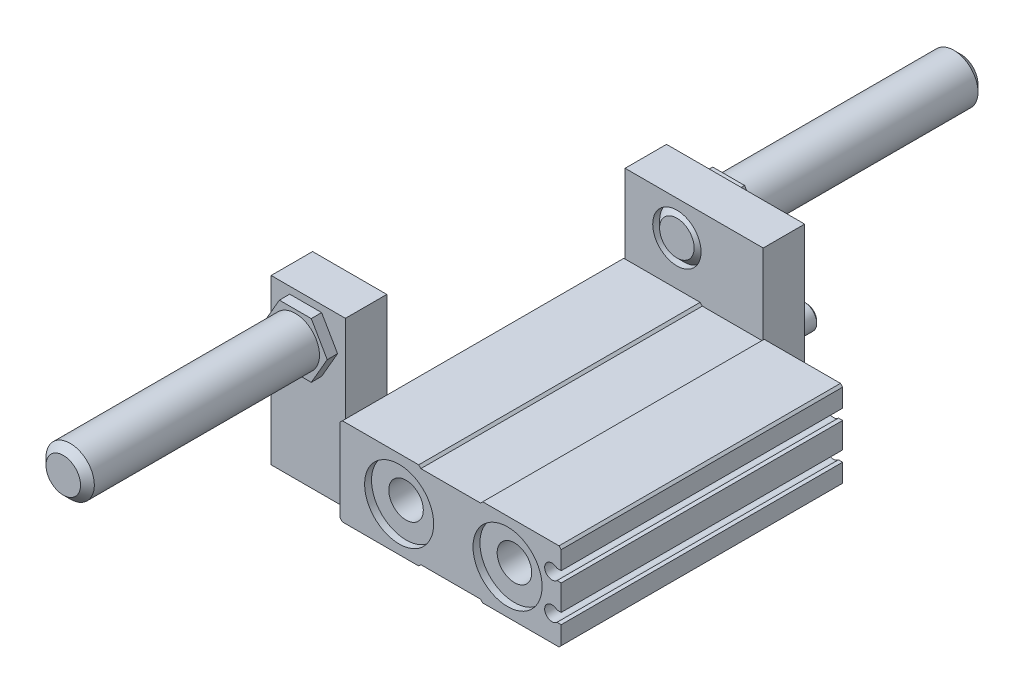
SolidWorks part; units mm, degrees
ref_plane "Front" through (0, 0, 0) normal (0, 0, 1) x (1, 0, 0)
ref_plane "Top" through (0, 0, 0) normal (0, 1, 0) x (1, 0, 0)
ref_plane "Right" through (0, 0, 0) normal (1, 0, 0) x (0, 0, -1)
ref_plane "Plane4" through (0, 0, 0) normal (0, 0, 1) x (-1, 0, 0)
sketch "Sketch1" plane through (0, 0, 48.65) normal (0, 0, 1) x (-1, 0, 0)
  line L0 (31.365, 12.6873) -> (32, 12.0523)
  line L1 (-8.636, 12.0523) -> (8.636, 12.0523)
  line L2 (31.365, 12.6873) -> (9.271, 12.6873)
  line L3 (-9.271, 12.6873) -> (-31.365, 12.6873)
  line L4 (8.636, 12.0523) -> (9.271, 12.6873)
  line L5 (-8.636, 12.0523) -> (-9.271, 12.6873)
  line L6 (-32, 12.0523) -> (-32, 6.7691)
  line L7 (-32, -12.0523) -> (-31.365, -12.6873)
  line L8 (-8.636, -12.0523) -> (-9.271, -12.6873)
  line L9 (-32, 3.6957) -> (-32, -3.6957)
  line L10 (-32, -6.7691) -> (-32, -12.0523)
  line L11 (-32, 12.0523) -> (-31.365, 12.6873)
  line L12 (32, 12.0523) -> (32, -12.0523)
  line L14 (-50, 0) -> (50, 0) construction
  line L15 (-9.271, -12.6873) -> (-31.365, -12.6873)
  line L16 (-30.7919, -6.7691) -> (-32, -6.7691)
  line L18 (-8.636, -12.0523) -> (8.636, -12.0523)
  line L19 (8.636, -12.0523) -> (9.271, -12.6873)
  line L20 (32, -12.0523) -> (31.365, -12.6873)
  line L22 (-32, 0) -> (32, 0) construction
  line L23 (0, 0) -> (0, 12.0523) construction
  line L26 (31.365, -12.6873) -> (9.271, -12.6873)
  line L27 (-30.7919, -3.6957) -> (-32, -3.6957)
  line L28 (-30.7919, 3.6957) -> (-32, 3.6957)
  line L29 (-30.7919, 6.7691) -> (-32, 6.7691)
  arc A0 (-30.7919, 3.6957) -> (-30.7919, 6.7691) centre (-29.3301, 5.2324) ccw
  arc A1 (-30.7919, -6.7691) -> (-30.7919, -3.6957) centre (-29.3301, -5.2324) ccw
  circle A2 centre (-16.4592, 0) radius 13.8938 construction
  dimension "D5" = 4.2418
  dimension "D9" = 5.2324
  dimension "D7" = 13.8938
  dimension "D1" = 25.3746
  dimension "D2" = 45
  dimension "D3" = 0.635
  dimension "D4" = 16.4592
  dimension "D6" = 18.542
  dimension "D8" = 3.0734
extrude "Base-Extrude" add sketch "Sketch1" along normal up to surface (81.5 mm away)
ref_plane "Plane8" through (0, 0, 46.65) normal (0, 0, 1) x (1, 0, 0)
sketch "Sketch2" plane through (0, 0, 48.65) normal (0, 0, -1) x (-1, 0, 0)
  line L0 (47.3, 0) -> (-47.3, 0) construction
  line L5 (0, 12.0523) -> (0, -12.0523) construction
  line L6 (8.636, 12.0523) -> (-8.636, 12.0523) construction
  line L7 (-8.636, -12.0523) -> (8.636, -12.0523) construction
  circle A0 centre (-16.4592, 0) radius 10
  circle A1 centre (14.9352, 0) radius 10
  dimension "D1" = 20
  dimension "D3" = 16.4592
  dimension "D2" = 31.3944
extrude "Cut-Extrude1" cut sketch "Sketch2" along normal up to surface (80.2 mm away)
sketch "Sketch4" plane through (0, 0, 46.65) normal (0, 0, 1) x (1, 0, 0)
  circle A2 centre (16.4592, 0) radius 10 construction
  circle A3 centre (-14.9352, 0) radius 10 construction
  circle A4 centre (16.4592, 0) radius 10
  circle A5 centre (-14.9352, 0) radius 10
extrude "Boss-Extrude1" add sketch "Sketch4" against normal blind 10
sketch "Sketch19" plane through (0, 0, 46.65) normal (0, 0, 1) x (1, 0, 0)
  circle A0 centre (16.4592, 0) radius 5
  circle A1 centre (-14.9352, 0) radius 5
  circle A2 centre (-14.9352, 0) radius 10 construction
  circle A3 centre (16.4592, 0) radius 10 construction
  dimension "D1" = 10
extrude "Cut-Extrude3" cut sketch "Sketch19" against normal up to next
hole_wizard "1/4-20 Tapped Hole1" positions "Sketch21" profile "Sketch20" tap size "1/4-20" standard "Ansi Inch"
sketch "Sketch21" plane through (0, -12.0523, 0) normal (0, -1, 0) x (1, 0, 0)
  point P0 (0, 23.15)
  point P1 (0, -6.85)
sketch "Sketch20" plane through (0, -12.0523, 23.15) normal (1, 0, 0) x (0, 0, -1)
  line L0 (0, 0) -> (0, 19.8218)
  line L1 (0, 19.8218) -> (2.5527, 18.288)
  line L2 (2.5527, 18.288) -> (2.5527, 11.938)
  line L3 (2.5527, 11.938) -> (3.175, 11.938)
  line L4 (3.175, 11.938) -> (3.175, 0)
  line L5 (3.175, 0) -> (0, 0)
  line L10 (0, 19.8218) -> (-2.5527, 18.288) construction
  line L11 (0, -6.35) -> (0, 107.95) construction
  dimension "Tap Drill Dia." = 5.1054
  dimension "Tap Drill Depth" = 18.288
  dimension "Thread Dia." = 6.35
  dimension "Thread Depth" = 11.938
  dimension "Drill Angle" = 118
hole_wizard "#10-32 Tapped Hole2" positions "Sketch23" profile "Sketch22" tap size "#10-32" standard "Ansi Inch"
sketch "Sketch23" plane through (0, 0, -32.85) normal (0, 0, -1) x (-1, 0, 0)
  line L0 (9.271, -12.6873) -> (31.365, -12.6873) construction
  point P0 (28, -7.5873)
  point P1 (28, 7.8127)
  point P2 (-4.5, -7.5873)
  point P3 (-4.5, 7.8127)
  dimension "D1" = 5.1
  dimension "D2" = 15.4
  dimension "D3" = 32.5
  dimension "D4" = 28
sketch "Sketch22" plane through (-28, -7.5873, -32.85) normal (1, 0, 0) x (0, 1, 0)
  line L0 (0, 0) -> (0, 15.0817)
  line L1 (0, 15.0817) -> (2.0193, 13.8684)
  line L2 (2.0193, 13.8684) -> (2.0193, 9.906)
  line L3 (2.0193, 9.906) -> (2.413, 9.906)
  line L4 (2.413, 9.906) -> (2.413, 0)
  line L5 (2.413, 0) -> (0, 0)
  line L10 (0, 15.0817) -> (-2.0193, 13.8684) construction
  line L11 (0, -6.35) -> (0, 107.95) construction
  dimension "Tap Drill Dia." = 4.0386
  dimension "Tap Drill Depth" = 13.8684
  dimension "Thread Dia." = 4.826
  dimension "Thread Depth" = 9.906
  dimension "Drill Angle" = 118
hole_wizard "Hole1" positions "Sketch25" profile "Sketch24" legacy
sketch "Sketch25" plane through (0, -12.6873, 0) normal (0, -1, 0) x (1, 0, 0)
  point P0 (-27.5, 36.15)
sketch "Sketch24" plane through (-27.5, -12.6873, 36.15) normal (1, 0, 0) x (0, 0, -1)
  line L0 (0, 0) -> (0, 5)
  line L1 (0, 5) -> (2.5, 5)
  line L2 (2.5, 5) -> (2.5, 0)
  line L3 (2.5, 0) -> (0, 0)
  line L4 (0, 110) -> (0, -10) construction
  dimension "Diameter" = 5
  dimension "Depth" = 5
sketch "Sketch27" plane through (0, -12.6873, 0) normal (0, -1, 0) x (1, 0, 0)
  line L0 (-32, -13.85) -> (-27.5, -13.85) construction
  line L1 (-32, 48.65) -> (-32, -32.85) construction
  line L2 (-32, -10.85) -> (-27.5, -10.85) construction
  line L3 (-32, -16.85) -> (-27.5, -16.85) construction
  line L4 (-30, -13.35) -> (-30, -14.35)
  line L5 (-25, -13.35) -> (-25, -14.35)
  arc A0 (-30, -14.35) -> (-25, -14.35) centre (-27.5, -14.35) ccw
  arc A1 (-25, -13.35) -> (-30, -13.35) centre (-27.5, -13.35) ccw
  dimension "D1" = 5
  dimension "D2" = 6
extrude "Cut-Extrude4" cut sketch "Sketch27" against normal blind 5
hole_wizard "#10-32 Tapped Hole1" positions "Sketch29" profile "Sketch28" tap size "#10-32" standard "Ansi Inch"
sketch "Sketch29" plane through (-32, 0, 0) normal (-1, 0, 0) x (0, 0, 1)
  line L0 (48.65, 12.0523) -> (48.65, -12.0523) construction
  line L1 (-32.85, -12.0523) -> (-32.85, 12.0523) construction
  line L2 (-32.85, -12.6873) -> (48.65, -12.6873) construction
  point P0 (27.85, -0.1873)
  point P1 (-24.85, -0.1873)
  dimension "D1" = 20.8
  dimension "D2" = 8
  dimension "D3" = 12.5
sketch "Sketch28" plane through (-32, -0.1873, 27.85) normal (0, 1, 0) x (0, 0, 1)
  line L0 (0, 0) -> (0, 14.8277)
  line L1 (0, 14.8277) -> (2.0193, 13.6144)
  line L2 (2.0193, 13.6144) -> (2.0193, 9.652)
  line L3 (2.0193, 9.652) -> (2.413, 9.652)
  line L4 (2.413, 9.652) -> (2.413, 0)
  line L5 (2.413, 0) -> (0, 0)
  line L10 (0, 14.8277) -> (-2.0193, 13.6144) construction
  line L11 (0, -6.35) -> (0, 107.95) construction
  dimension "Tap Drill Dia." = 4.0386
  dimension "Tap Drill Depth" = 13.6144
  dimension "Thread Dia." = 4.826
  dimension "Thread Depth" = 9.652
  dimension "Drill Angle" = 118
sketch "Sketch30" plane through (0, 0, -32.85) normal (0, 0, -1) x (-1, 0, 0)
  line L0 (-8.636, -12.0523) -> (8.636, -12.0523) construction
  line L1 (-9, 35.4477) -> (31, 35.4477)
  line L2 (-9, 35.4477) -> (-9, -11.5523)
  line L3 (-9, -11.5523) -> (31, -11.5523)
  line L4 (31, 35.4477) -> (31, -11.5523)
  line L5 (32, -12.0523) -> (32, 12.0523) construction
  dimension "D1" = 0.5
  dimension "D2" = 1
  dimension "D3" = 47
  dimension "D4" = 40
extrude "Boss-Extrude2" add sketch "Sketch30" along normal blind 12
sketch "Sketch31" plane through (0, 0, -44.85) normal (0, 0, -1) x (-1, 0, 0)
  line L0 (25.2376, 25.4477) -> (20.6188, 33.4477)
  line L1 (20.6188, 33.4477) -> (11.3812, 33.4477)
  line L2 (11.3812, 33.4477) -> (6.7624, 25.4477)
  line L3 (6.7624, 25.4477) -> (11.3812, 17.4477)
  line L4 (11.3812, 17.4477) -> (20.6188, 17.4477)
  line L5 (20.6188, 17.4477) -> (25.2376, 25.4477)
  line L6 (31, 35.4477) -> (-9, 35.4477) construction
  line L7 (31, -11.5523) -> (31, 35.4477) construction
  circle A0 centre (16, 25.4477) radius 9.2376 construction
  dimension "D1" = 10
  dimension "D2" = 15
  dimension "D3" = 16
extrude "Boss-Extrude3" add sketch "Sketch31" along normal blind 3
sketch "Sketch35" plane through (0, 0, -44.85) normal (0, 0, -1) x (-1, 0, 0)
  circle A0 centre (28, 7.8127) radius 3.5
  circle A1 centre (-4.5, 7.8127) radius 3.5
  circle A2 centre (-4.5, -7.5873) radius 3.5
  circle A3 centre (28, -7.5873) radius 3.5
  circle A4 centre (28, -7.5873) radius 2.413 construction
  circle A7 centre (-4.5, 7.8127) radius 2.413 construction
  circle A8 centre (-4.5, -7.5873) radius 2.413 construction
  circle A9 centre (28, 7.8127) radius 2.413 construction
  dimension "D1" = 7
extrude "Boss-Extrude5" add sketch "Sketch35" along normal blind 5
chamfer "Chamfer2" distance 0.5 angle 45 4 edges at (-31.5, 7.8127, -49.85) (-31.5, -7.5873, -49.85) (1, -7.5873, -49.85) (1, 7.8127, -49.85)
ref_plane "Plane9" through (0, 0, 34.65) normal (0, 0, 1) x (1, 0, 0)
sketch "Sketch36" plane through (0, 0, 34.65) normal (0, 0, 1) x (1, 0, 0)
  line L0 (-32.5, 36.8127) -> (-32.5, 10.6873)
  line L1 (-54, 36.8127) -> (-32.5, 36.8127)
  line L2 (-54, 36.8127) -> (-54, -10.6873)
  line L3 (-54, -10.6873) -> (-32, -10.6873)
  line L4 (-32, 10.6873) -> (-32, -10.6873)
  line L5 (-32.5, 10.6873) -> (-32, 10.6873)
  line L7 (-32, 36.3127) -> (-32, -10.1873) construction
  line L8 (-31.365, -12.6873) -> (-9.271, -12.6873) construction
  line L11 (-30.1528, 12.6873) -> (-32, 12.6873) construction
  dimension "D1" = 22
  dimension "D2" = 0.5
  dimension "D3" = 47.5
  dimension "D4" = 2
  dimension "D5" = 2
extrude "Boss-Extrude6" add sketch "Sketch36" along normal blind 12
sketch "Sketch37" plane through (0, 0, 46.65) normal (0, 0, 1) x (1, 0, 0)
  line L0 (-54, 36.8127) -> (-54, -10.6873) construction
  line L1 (-39.3812, 34.8127) -> (-48.6188, 34.8127)
  line L2 (-48.6188, 34.8127) -> (-53.2376, 26.8127)
  line L3 (-53.2376, 26.8127) -> (-48.6188, 18.8127)
  line L4 (-48.6188, 18.8127) -> (-39.3812, 18.8127)
  line L5 (-39.3812, 18.8127) -> (-34.7624, 26.8127)
  line L8 (-34.7624, 26.8127) -> (-39.3812, 34.8127)
  line L9 (-32.5, 36.8127) -> (-54, 36.8127) construction
  circle A0 centre (-44, 26.8127) radius 8 construction
  dimension "D1" = 10
  dimension "D2" = 10
  dimension "D3" = 16
extrude "Boss-Extrude7" add sketch "Sketch37" along normal blind 3
sketch "Sketch38" plane through (0, 0, 49.65) normal (0, 0, 1) x (1, 0, 0)
  line L0 (-34.7624, 26.8127) -> (-39.3812, 34.8127) construction
  line L1 (-53.2376, 26.8127) -> (-48.6188, 18.8127) construction
  line L2 (-39.3812, 34.8127) -> (-48.6188, 34.8127) construction
  circle A0 centre (-44, 26.8127) radius 8 construction
  circle A1 centre (-44, 26.8127) radius 7
  dimension "D1" = 14
ref_plane "Plane11" through (0, 26.8127, 0) normal (0, 1, 0) x (-1, 0, 0)
extrude "Cut-Extrude7" cut sketch "Sketch38" against normal up to next
sketch "Sketch44" plane through (0, 26.8127, 0) normal (0, 1, 0) x (-1, 0, 0)
  line L0 (44, 49.65) -> (44, 34.65) construction
  line L1 (39.3812, 49.65) -> (48.6188, 49.65) construction
  line L2 (9.7125, 34.65) -> (-9.7125, 34.65) construction
  line L4 (44, 116.85) -> (51, 116.85)
  line L5 (44, 116.85) -> (44, 34.65)
  line L6 (44, 34.65) -> (49, 34.65)
  line L7 (51, 116.85) -> (51, 36.65)
  line L8 (51, 36.65) -> (49, 34.65)
  line L10 (51, 34.65) -> (51, 49.65) construction
  line L11 (32.5, 34.65) -> (54, 34.65) construction
  line L12 (32.5, 46.65) -> (54, 46.65) construction
  dimension "D1" = 70.2
  dimension "D2" = 45
  dimension "D3" = 2
revolve "Boss-Revolve1" add sketch "Sketch44" angle 360 about L0
sketch "Sketch46" plane through (0, 0, -47.85) normal (0, 0, -1) x (-1, 0, 0)
  line L0 (25.2376, 25.4477) -> (20.6188, 33.4477) construction
  line L1 (11.3812, 17.4477) -> (20.6188, 17.4477) construction
  line L2 (11.3812, 33.4477) -> (6.7624, 25.4477) construction
  circle A0 centre (16, 25.4477) radius 8 construction
  circle A1 centre (16, 25.4477) radius 7
  dimension "D1" = 14
extrude "Cut-Extrude8" cut sketch "Sketch46" against normal up to next
ref_plane "Plane12" through (0, 25.4477, 0) normal (0, 1, 0) x (-1, 0, 0)
sketch "Sketch47" plane through (0, 25.4477, 0) normal (0, 1, 0) x (-1, 0, 0)
  line L0 (31, -32.85) -> (-9, -32.85) construction
  line L2 (23, -47.85) -> (23, -32.85) construction
  line L3 (21, -32.85) -> (16, -32.85)
  line L4 (16, -32.85) -> (16, -115.05)
  line L5 (23, -115.05) -> (23, -34.85)
  line L6 (16, -32.85) -> (16, -115.05) construction
  line L7 (16, -115.05) -> (23, -115.05)
  line L8 (23, -34.85) -> (21, -32.85)
  line L9 (31, -44.85) -> (-9, -44.85) construction
  line L10 (16, -32.85) -> (16, -47.85) construction
  dimension "D1" = 45
  dimension "D2" = 2
  dimension "D3" = 70.2
revolve "Boss-Revolve2" add sketch "Sketch47" angle 360 about L6
chamfer "Chamfer3" distance 2 angle 45 2 edges at (-9, 25.4477, -115.05) (-37, 26.8127, 116.85)
